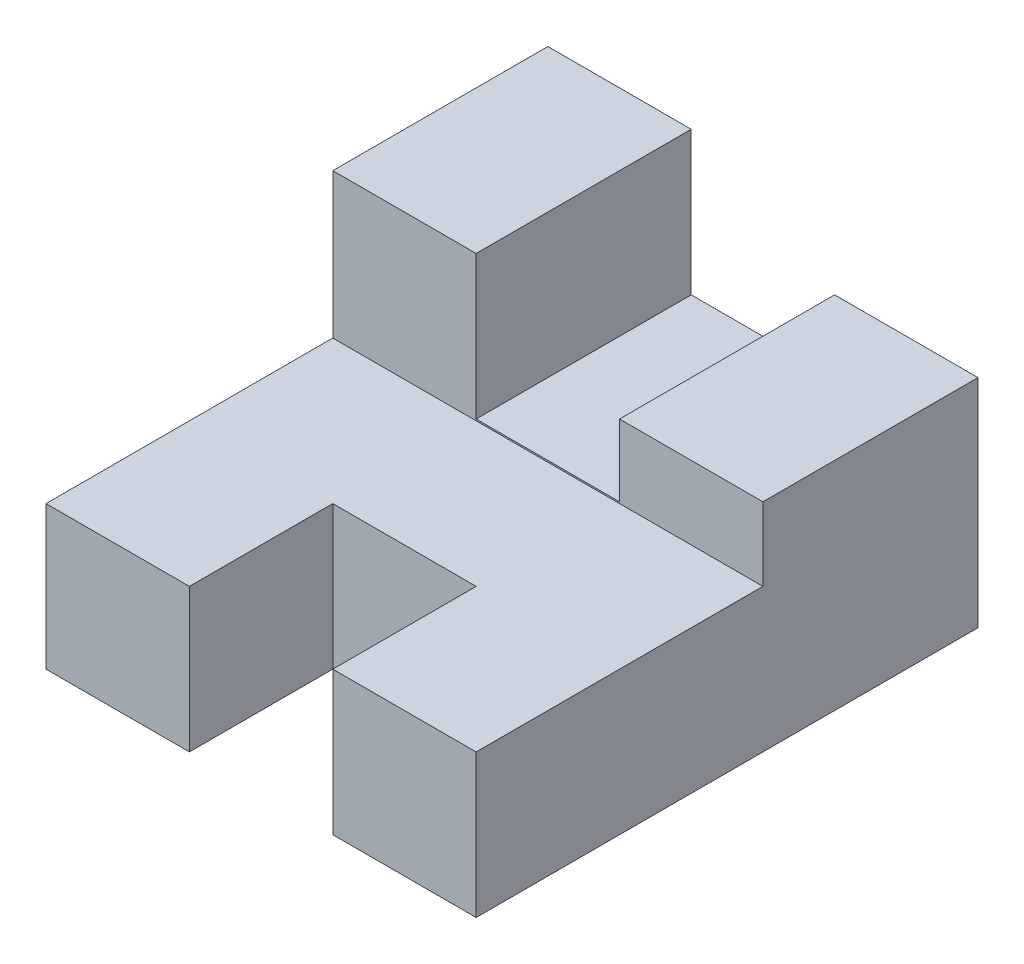
SolidWorks part; units mm, degrees
ref_plane "Plano frontal" through (0, 0, 0) normal (0, 0, 1) x (1, 0, 0)
ref_plane "Plano superior" through (0, 0, 0) normal (0, 1, 0) x (1, 0, 0)
ref_plane "Plano direito" through (0, 0, 0) normal (1, 0, 0) x (0, 0, -1)
sketch "Esboço1" plane through (0, 0, 0) normal (0, 0, 1) x (1, 0, 0)
  line L1 (0, 0) -> (60, 0)
  line L2 (0, 0) -> (0, 20)
  line L3 (0, 20) -> (60, 20)
  line L4 (60, 0) -> (60, 20)
  dimension "D1" = 60
  dimension "D2" = 20
extrude "Ressalto-extrusão1" add sketch "Esboço1" along normal blind 40
sketch "Esboço2" plane through (0, 20, 0) normal (0, 1, 0) x (1, 0, 0)
  line L0 (60, -40) -> (0, -40) construction
  line L4 (20, -40) -> (20, -20)
  line L5 (20, -20) -> (40, -20)
  line L7 (20, -40) -> (40, -40)
  line L8 (40, -20) -> (40, -40)
extrude "Corte-extrusão1" cut sketch "Esboço2" against normal blind 40
sketch "Esboço3" plane through (0, 0, 0) normal (0, 0, -1) x (-1, 0, 0)
  line L1 (-60, 0) -> (0, 0)
  line L2 (-60, 0) -> (-60, 40.2165)
  line L3 (-60, 40.2165) -> (0, 40.2165)
  line L4 (0, 0) -> (0, 40.2165)
extrude "Ressalto-extrusão2" add sketch "Esboço3" along normal blind 30
sketch "Esboço4" plane through (0, 40.2165, 0) normal (0, 1, 0) x (1, 0, 0)
  line L0 (60, 0) -> (0, 0) construction
  line L4 (20, 30) -> (20, 0)
  line L5 (0, 0) -> (60, 0) construction
  line L6 (20, 30) -> (40, 30)
  line L8 (20, 0) -> (40, 0)
  line L9 (40, 30) -> (40, 0)
extrude "Corte-extrusão4" cut sketch "Esboço4" against normal blind 20
sketch "Esboço7" plane through (0, 40.2165, 0) normal (0, 1, 0) x (1, 0, 0)
  line L1 (40, 30) -> (60, 30)
  line L2 (40, 30) -> (40, 0)
  line L3 (40, 0) -> (60, 0)
  line L4 (60, 30) -> (60, 0)
extrude "Corte-extrusão6" cut sketch "Esboço7" against normal blind 10
